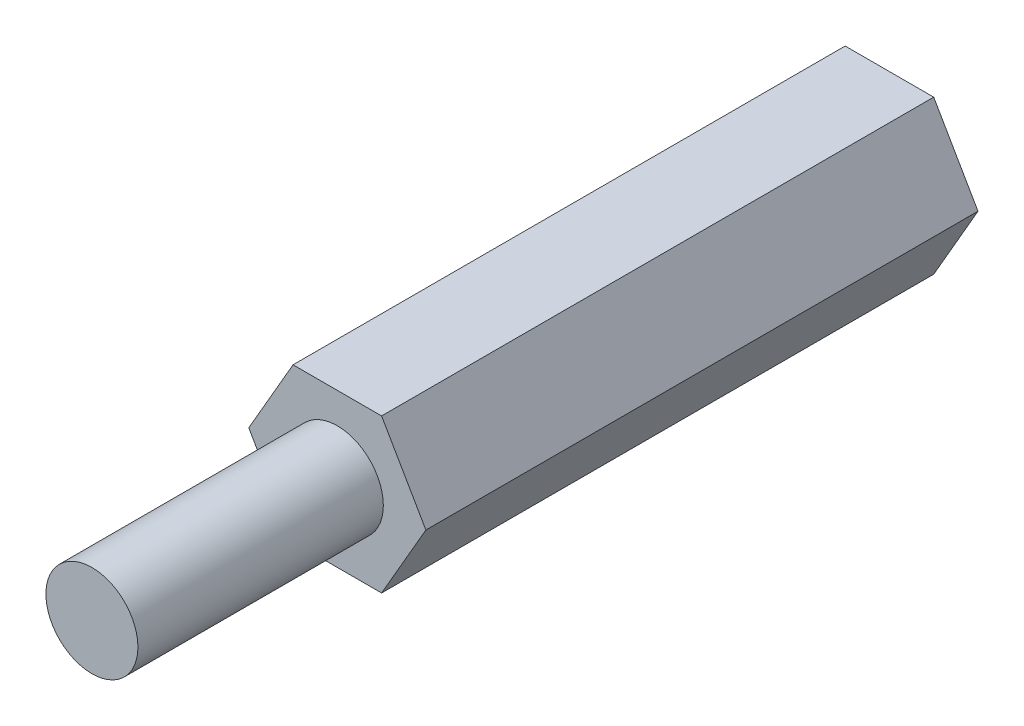
SolidWorks part; units mm, degrees
material "Brass"
ref_plane "Front Plane" through (0, 0, 0) normal (0, 0, 1) x (1, 0, 0)
ref_plane "Top Plane" through (0, 0, 0) normal (0, 1, 0) x (1, 0, 0)
ref_plane "Right Plane" through (0, 0, 0) normal (1, 0, 0) x (0, 0, -1)
sketch "Sketch1" plane through (0, 0, 0) normal (0, 0, 1) x (1, 0, 0)
  line L1 (-1.4434, 2.5) -> (-2.8868, 0)
  line L2 (-2.8868, 0) -> (-1.4434, -2.5)
  line L3 (-1.4434, -2.5) -> (1.4434, -2.5)
  line L4 (1.4434, -2.5) -> (2.8868, 0)
  line L5 (2.8868, 0) -> (1.4434, 2.5)
  line L6 (1.4434, 2.5) -> (-1.4434, 2.5)
  circle A0 centre (0, 0) radius 2.5 construction
  dimension "D1" = 5
extrude "Boss-Extrude1" add sketch "Sketch1" along normal blind 18
sketch "Sketch2" plane through (0, 0, 18) normal (0, 0, 1) x (1, 0, 0)
  circle A0 centre (0, 0) radius 1.5
extrude "Boss-Extrude2" add sketch "Sketch2" along normal blind 8
cosmetic thread "Cosmetic Thread1" parameters "D2"=2.439
hole_wizard "M3x0.5 Tapped Hole1" positions "Sketch6" profile "Sketch5" tap size "M3x0.5" standard "ANSI Metric"
sketch "Sketch6" plane through (0, 0, 0) normal (0, 0, -1) x (-1, 0, 0)
  point P0 (0, 0)
sketch "Sketch5" plane through (0, 0, 0) normal (1, 0, 0) x (0, 1, 0)
  line L0 (0, 0) -> (0, 8.7511)
  line L1 (0, 8.7511) -> (1.25, 8)
  line L2 (1.25, 8) -> (1.25, 0)
  line L5 (1.25, 0) -> (0, 0)
  line L10 (0, 8.7511) -> (-1.25, 8) construction
  line L11 (0, -6.35) -> (0, 107.95) construction
  dimension "Tap Drill Dia." = 2.5
  dimension "Tap Drill Depth" = 8
  dimension "Drill Angle" = 118
cosmetic thread "Hole Thread1" parameters "D1"=8, "D2"=3
